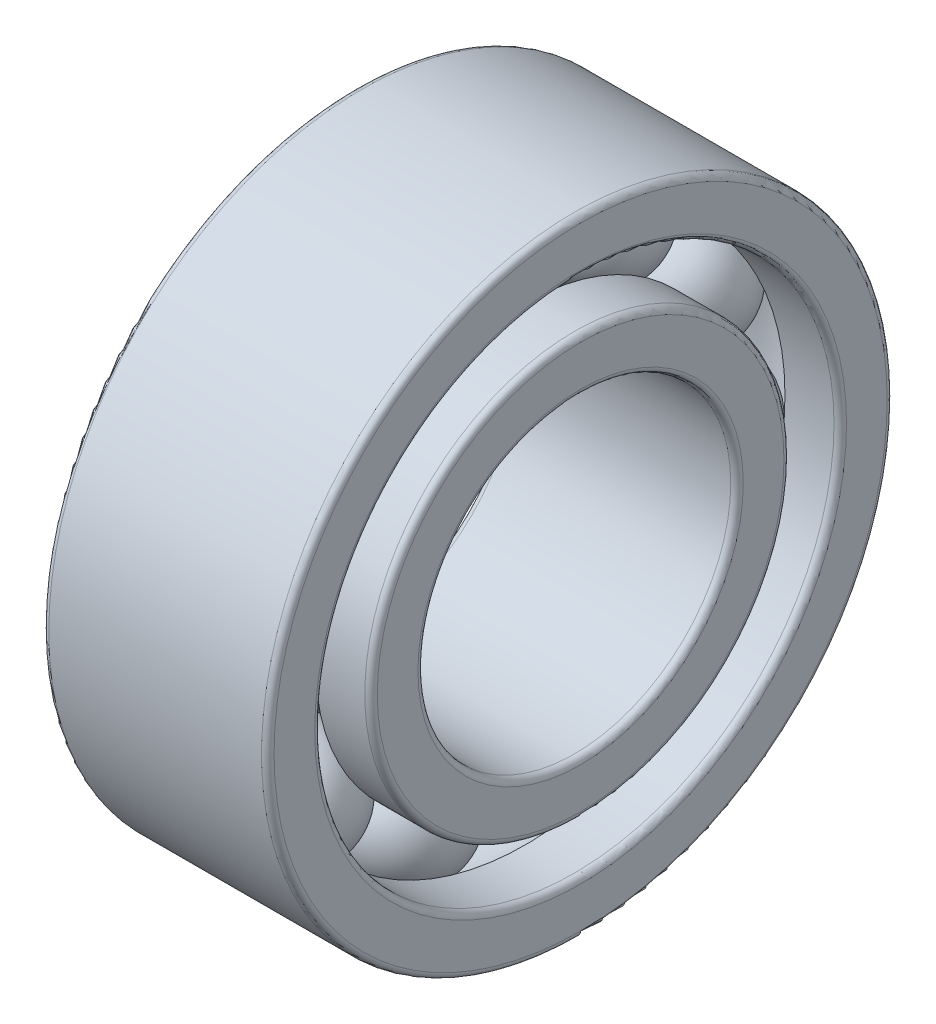
SolidWorks part; units mm, degrees
ref_plane "Ön Düzlem" through (0, 0, 0) normal (0, 0, 1) x (1, 0, 0)
ref_plane "Üst Düzlem" through (0, 0, 0) normal (0, 1, 0) x (1, 0, 0)
ref_plane "Sağ Düzlem" through (0, 0, 0) normal (1, 0, 0) x (0, 0, -1)
sketch "Sketch1" plane through (0, 0, 0) normal (0, 0, 1) x (1, 0, 0)
  line L0 (0, 0) -> (0, 16.75) construction
  line L1 (0, 25) -> (-18, 25)
  line L2 (-18, 25) -> (-18, 20.75)
  line L3 (-18, 12.5) -> (0, 12.5)
  line L4 (-18, 18.75) -> (0, 18.75) construction
  line L5 (-18, 20.75) -> (-13.5826, 20.75)
  line L6 (-18, 16.75) -> (-13.5826, 16.75)
  line L7 (0, 12.5) -> (0, 16.75)
  line L8 (-4.4174, 16.75) -> (0, 16.75)
  line L9 (-4.4174, 20.75) -> (0, 20.75)
  line L10 (-18, 16.75) -> (-18, 12.5)
  line L11 (0, 20.75) -> (0, 25) construction
  line L12 (0, 20.75) -> (0, 25)
  line L13 (0, 0) -> (-26.8032, 0) construction
  arc A0 (-13.5826, 16.75) -> (-4.4174, 16.75) centre (-9, 18.75) ccw
  arc A1 (-4.4174, 20.75) -> (-13.5826, 20.75) centre (-9, 18.75) ccw
  dimension "D4" = 10
  dimension "D1" = 12.5
  dimension "D2" = 25
  dimension "D3" = 18
  dimension "D5" = 2
revolve "Revolve1" add sketch "Sketch1" angle 360 about L13
sketch "Sketch2" plane through (0, 0, 0) normal (0, 0, 1) x (1, 0, 0)
  line L0 (0, 0) -> (0, 18.75) construction
  line L1 (0, -12.5) -> (0, 12.5) construction
  line L2 (0, -20.75) -> (0, 20.75) construction
  line L3 (0, 18.75) -> (-18, 18.75) construction
  line L4 (-18, 20.75) -> (-18, -20.75) construction
  line L5 (-13.75, 18.75) -> (-4.25, 18.75)
  arc A0 (-13.75, 18.75) -> (-4.25, 18.75) centre (-9, 18.75) ccw
  dimension "D2" = 9.5
  dimension "D1" = 18.75
revolve "Revolve2" add sketch "Sketch2" angle 360 about L5
pattern_circular "CirPattern4" count 11 over 360 about axis through (0, 0, 0) along (1, 0, 0) of bodies 103
fillet "Fillet1" radius 0.5 4 edges at (-18, 0, -12.5) (0, 0, -12.5) (0, 0, -16.75) (-18, 0, -16.75)
fillet "Fillet2" radius 0.5 4 edges at (-18, 0, -20.75) (0, 0, -20.75) (0, 0, -25) (-18, 0, -25)
